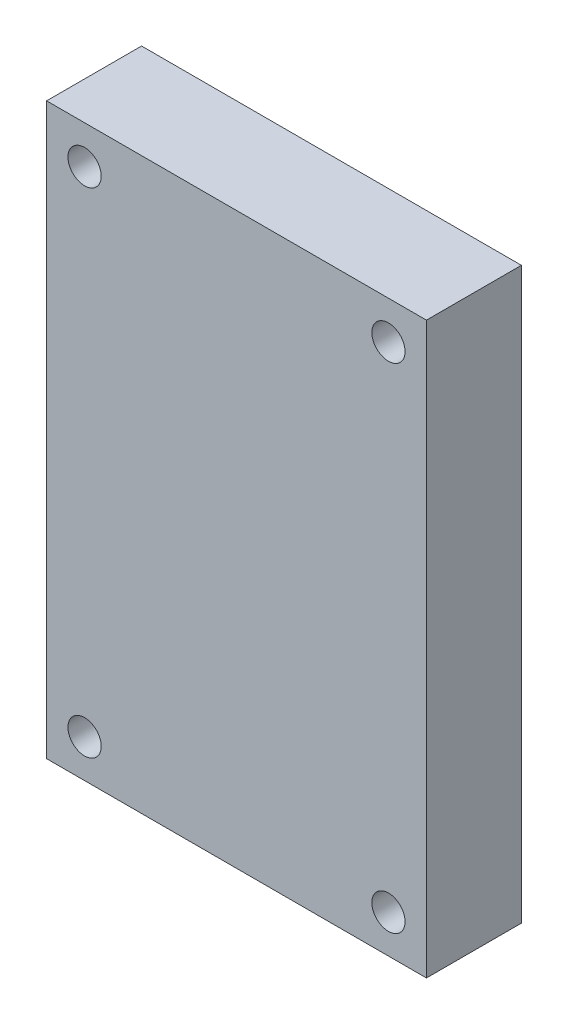
SolidWorks part; units mm, degrees
ref_plane "Płaszczyzna przednia" through (0, 0, 0) normal (0, 0, 1) x (1, 0, 0)
ref_plane "Płaszczyzna górna" through (0, 0, 0) normal (0, 1, 0) x (1, 0, 0)
ref_plane "Płaszczyzna prawa" through (0, 0, 0) normal (1, 0, 0) x (0, 0, -1)
sketch "Sketch1" plane through (0, 0, 0) normal (0, 0, 1) x (1, 0, 0)
  line L1 (-20, -30) -> (20, -30)
  line L2 (-20, -30) -> (-20, 30)
  line L3 (-20, 30) -> (20, 30)
  line L4 (20, -30) -> (20, 30)
  line L5 (-20, -30) -> (20, 30) construction
  line L6 (-20, 30) -> (20, -30) construction
  line L7 (16, -26) -> (-16, -26) construction
  line L8 (16, -26) -> (16, 26) construction
  line L9 (16, 26) -> (-16, 26) construction
  line L10 (-16, -26) -> (-16, 26) construction
  line L11 (16, -26) -> (-16, 26) construction
  line L12 (16, 26) -> (-16, -26) construction
  circle A0 centre (-16, 26) radius 1.75
  circle A1 centre (16, 26) radius 1.75
  circle A2 centre (16, -26) radius 1.75
  circle A3 centre (-16, -26) radius 1.75
  point P0 (0, 0)
  point P6 (0, 0)
  dimension "D5" = 3.5
  dimension "D1" = 60
  dimension "D2" = 40
  dimension "D3" = 32
  dimension "D4" = 52
extrude "Boss-Extrude1" add sketch "Sketch1" along normal blind 10
sketch "Sketch3" plane through (0, 0, 0) normal (0, 0, 1) x (1, 0, 0)
  circle A0 centre (16, 26) radius 3
  circle A1 centre (-16, 26) radius 3
  circle A2 centre (16, -26) radius 3
  circle A3 centre (-16, -26) radius 3
  dimension "D1" = 6
  dimension "D2" = 6
  dimension "D3" = 6
  dimension "D4" = 6
extrude "Cut-Extrude1" cut sketch "Sketch3" along normal blind 5
